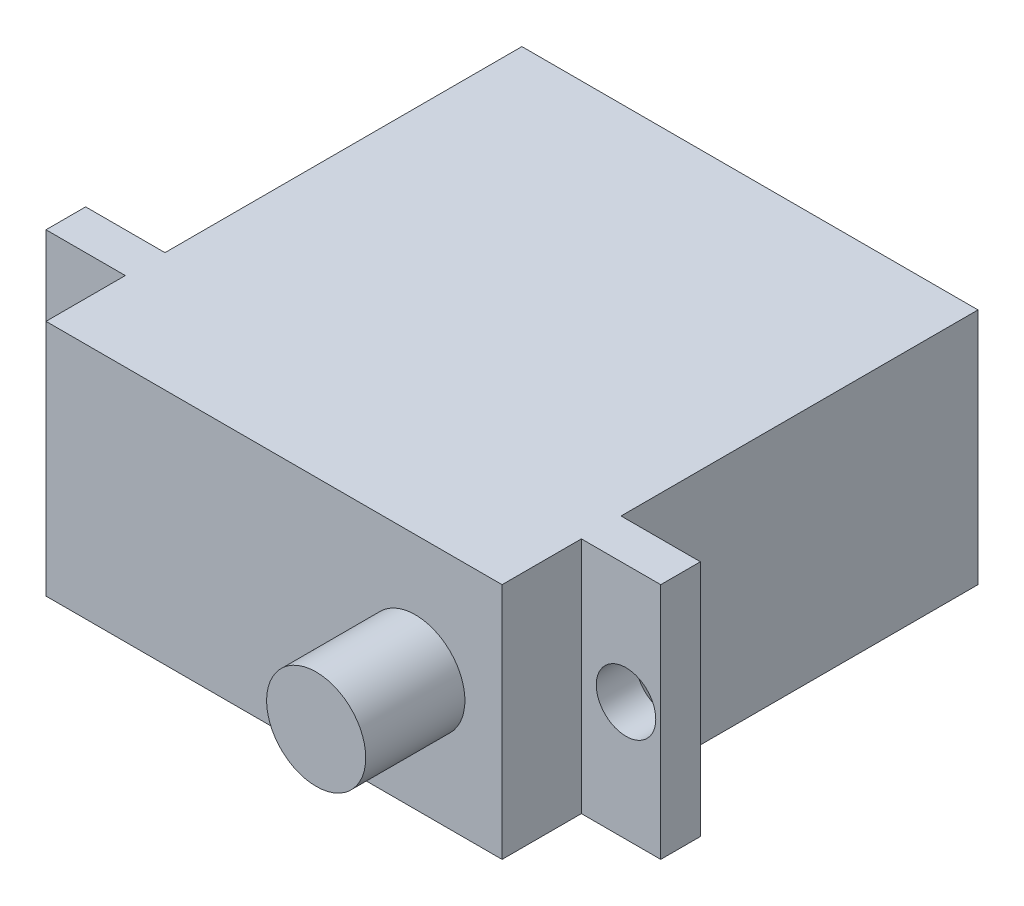
SolidWorks part; units mm, degrees
ref_plane "前视基准面" through (0, 0, 0) normal (0, 0, 1) x (1, 0, 0)
ref_plane "上视基准面" through (0, 0, 0) normal (0, 1, 0) x (1, 0, 0)
ref_plane "右视基准面" through (0, 0, 0) normal (1, 0, 0) x (0, 0, -1)
sketch "草图1" plane through (0, 0, 0) normal (0, 0, 1) x (1, 0, 0)
  line L1 (0, 0) -> (23, 0)
  line L2 (0, 0) -> (0, 12)
  line L3 (0, 12) -> (23, 12)
  line L4 (23, 0) -> (23, 12)
  dimension "D1" = 23
  dimension "D2" = 12
extrude "凸台-拉伸1" add sketch "草图1" along normal blind 20
sketch "草图2" plane through (0, 0, 20) normal (0, 0, 1) x (1, 0, 0)
  line L0 (23, 12) -> (0, 12) construction
  line L1 (0, 12) -> (-4, 12)
  line L2 (0, 12) -> (0, 0)
  line L3 (0, 0) -> (-4, 0)
  line L4 (-4, 12) -> (-4, 0)
  line L5 (23, 12) -> (27, 12)
  line L6 (23, 12) -> (23, 0)
  line L7 (23, 0) -> (27, 0)
  line L8 (27, 12) -> (27, 0)
  circle A0 centre (-2.25, 6) radius 1.5
  circle A1 centre (25.25, 6) radius 1.5
  point P16 (11.5, 12)
  dimension "D5" = 3
  dimension "D6" = 3
  dimension "D1" = 4
  dimension "D2" = 4
  dimension "D3" = 13.75
  dimension "D4" = 13.75
extrude "凸台-拉伸2" add sketch "草图2" against normal blind 2
sketch "草图3" plane through (0, 0, 20) normal (0, 0, 1) x (1, 0, 0)
  line L0 (27, 12) -> (-4, 12) construction
  line L1 (0, 0) -> (23, 0)
  line L2 (0, 0) -> (0, 12)
  line L3 (0, 12) -> (23, 12)
  line L4 (23, 0) -> (23, 12)
  dimension "D1" = 23
extrude "凸台-拉伸3" add sketch "草图3" along normal blind 4
sketch "草图4" plane through (0, 0, 24) normal (0, 0, 1) x (1, 0, 0)
  circle A0 centre (18.6238, 6) radius 2.5
  dimension "D1" = 5
extrude "凸台-拉伸4" add sketch "草图4" along normal blind 5
equation "\"D3@草图2\"=27.5/2"
equation "\"D4@草图2\"=\"D3@草图2\""
